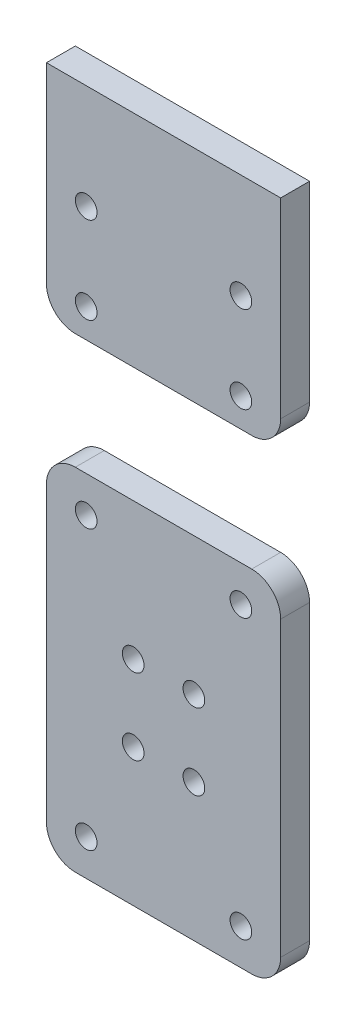
SolidWorks part; units mm, degrees
ref_plane "Front Plane" through (0, 0, 0) normal (0, 0, 1) x (1, 0, 0)
ref_plane "Top Plane" through (0, 0, 0) normal (0, 1, 0) x (1, 0, 0)
ref_plane "Right Plane" through (0, 0, 0) normal (1, 0, 0) x (0, 0, -1)
sketch "Sketch1" plane through (0, 0, 0) normal (0, 0, 1) x (1, 0, 0)
  line L0 (4, 44.7) -> (4, 52.7)
  line L1 (0, -0.06) -> (16.2, -0.06) construction
  line L2 (8.1, -0.06) -> (8.1, 67.93) construction
  line L3 (6, 12.44) -> (10.2, 12.44) construction
  line L4 (6, 20.44) -> (10.2, 20.44)
  line L5 (6, 44.7) -> (6, 52.7)
  line L6 (0, 54.7) -> (0, 67.93)
  line L7 (6, 44.7) -> (10.2, 44.7)
  line L8 (6, 52.7) -> (10.2, 52.7)
  line L9 (2, 44.7) -> (4, 44.7)
  line L10 (0, 67.93) -> (16.2, 67.93)
  line L11 (2, 20.44) -> (4, 20.44)
  line L12 (0, 22.44) -> (0, 42.7)
  line L13 (16.2, 12.44) -> (12.2, 12.44) construction
  line L14 (12.2, 20.44) -> (12.2, 12.44)
  line L15 (10.2, 12.44) -> (10.2, 20.44)
  line L16 (16.2, 12.44) -> (16.2, -0.06) construction
  line L17 (14.2, 52.7) -> (12.2, 52.7)
  line L18 (16.2, 22.44) -> (16.2, 42.7)
  line L19 (14.2, 20.44) -> (12.2, 20.44)
  line L20 (14.2, 44.7) -> (12.2, 44.7)
  line L21 (16.2, 54.7) -> (16.2, 67.93)
  line L22 (10.2, 44.7) -> (10.2, 52.7)
  line L23 (12.2, 44.7) -> (12.2, 52.7)
  line L24 (4, 12.44) -> (6, 12.44)
  line L25 (10.2, 12.44) -> (12.2, 12.44)
  line L36 (2, 52.7) -> (4, 52.7)
  line L46 (0, 12.44) -> (0, -0.06) construction
  line L47 (6, 12.44) -> (6, 20.44)
  line L48 (4, 20.44) -> (4, 12.44)
  line L49 (0, 12.44) -> (4, 12.44) construction
  circle A0 centre (2.75, 60.7) radius 0.75
  circle A1 centre (13.35, 9.94) radius 0.75 construction
  circle A2 centre (13.35, 3.94) radius 0.75 construction
  circle A3 centre (13.45, 54.7) radius 0.75
  arc A4 (16.2, 54.7) -> (14.2, 52.7) centre (14.2, 54.7) cw
  circle A5 centre (13.45, 42.2) radius 0.75
  circle A6 centre (13.45, 22.94) radius 0.75
  circle A7 centre (10.2, 29.94) radius 0.75
  arc A8 (16.2, 22.44) -> (14.2, 20.44) centre (14.2, 22.44) cw
  circle A9 centre (6, 35.2) radius 0.75
  arc A10 (14.2, 44.7) -> (16.2, 42.7) centre (14.2, 42.7) cw
  circle A11 centre (13.45, 60.7) radius 0.75
  circle A12 centre (10.2, 35.2) radius 0.75
  arc A27 (2, 44.7) -> (0, 42.7) centre (2, 42.7) ccw
  arc A31 (0, 22.44) -> (2, 20.44) centre (2, 22.44) ccw
  circle A33 centre (6, 29.94) radius 0.75
  circle A35 centre (2.75, 22.94) radius 0.75
  circle A37 centre (2.75, 42.2) radius 0.75
  arc A43 (0, 54.7) -> (2, 52.7) centre (2, 54.7) ccw
  circle A45 centre (2.75, 54.7) radius 0.75
  circle A46 centre (2.85, 3.94) radius 0.75 construction
  circle A47 centre (2.85, 9.94) radius 0.75 construction
  point P30 (8.1, 20.44)
  point P31 (8.1, 12.44)
  point P47 (8.1, 52.7)
  point P48 (8.1, 44.7)
  dimension "D10" = 1.5
  dimension "D11" = 2
  dimension "D18" = 2
  dimension "D26" = 2
  dimension "D28" = 6
  dimension "D1" = 8
  dimension "D2" = 8
  dimension "D3" = 4
  dimension "D4" = 6
  dimension "D5" = 2.5
  dimension "D6" = 4
  dimension "D7" = 2.85
  dimension "D8" = 2.85
  dimension "D9" = 2
  dimension "D12" = 2.5
  dimension "D13" = 2.75
  dimension "D14" = 9.5
  dimension "D15" = 6
  dimension "D16" = 2
  dimension "D17" = 2
  dimension "D19" = 2.5
  dimension "D20" = 2.75
  dimension "D21" = 2
  dimension "D22" = 2
  dimension "D23" = 2.75
  dimension "D24" = 24.26
  dimension "D25" = 9.5
  dimension "D27" = 2
  dimension "D29" = 2
  dimension "D30" = 2.75
  dimension "D31" = 8.1
  dimension "D32" = 15.23
  dimension "D33" = 6
extrude "Boss-Extrude1" add sketch "Sketch1" along normal blind 2
sketch "Sketch2" plane through (0, 0, 2) normal (0, 0, 1) x (1, 0, 0)
  line L0 (12.2, 12.44) -> (4, 12.44)
  line L1 (4, 20.44) -> (12.2, 20.44)
  line L2 (12.2, 20.44) -> (12.2, 12.44)
  line L3 (4, 12.44) -> (4, 20.44)
  line L4 (4, 52.7) -> (12.2, 52.7)
  line L5 (12.2, 52.7) -> (12.2, 44.7)
  line L6 (12.2, 44.7) -> (4, 44.7)
  line L7 (4, 44.7) -> (4, 52.7)
extrude "Cut-Extrude1" cut sketch "Sketch2" against normal up to surface (2 mm away) up to face at (3.5, 42.2, 0)
equation "\"D24@Sketch1\"= \"HL@parametersSketch@prostheticParameters.SLDPRT\" * 0.196 - 4 - 8'Thumb PIP Length"
equation "\"D32@Sketch1\" = \"HL@parametersSketch@prostheticParameters.SLDPRT\" * 0.158 - 4 - 10'Thumb DIP Length - Gap Fingertip"
equation "\"D31@Sketch1\"= \"fingerWidth@parametersSketch@prostheticParameters.SLDPRT\" / 2'Finger Width"
